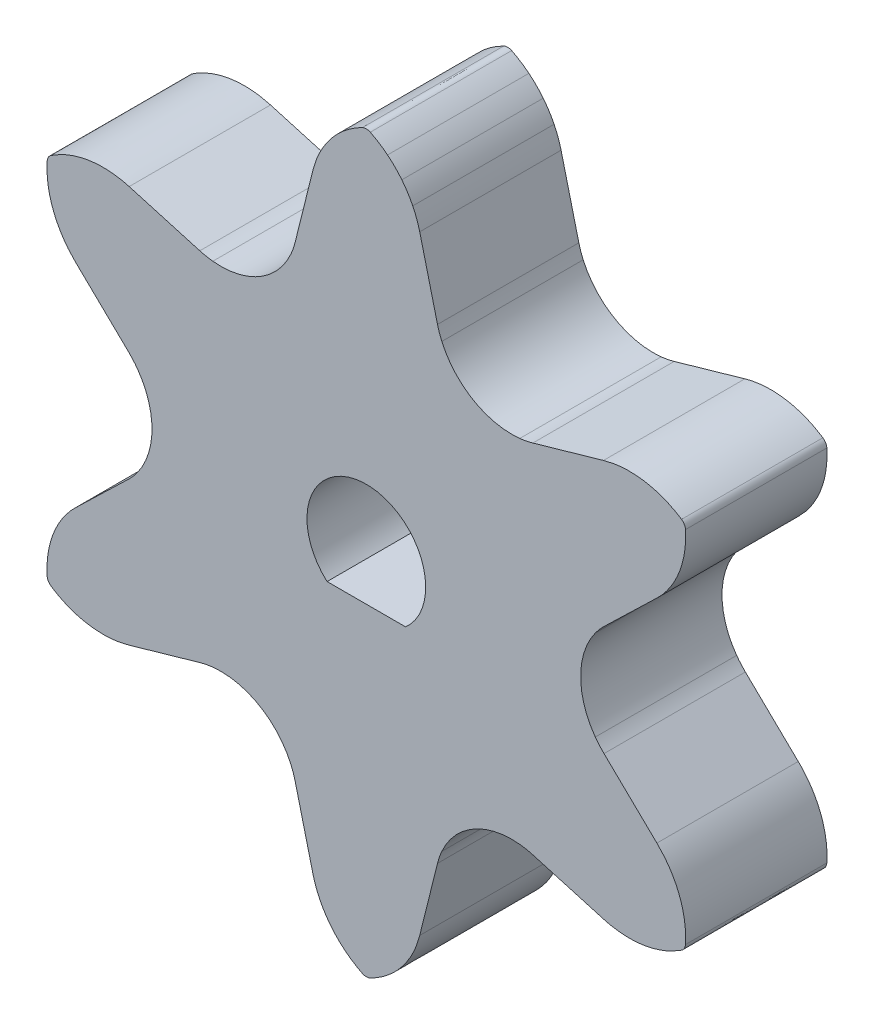
SolidWorks part; units mm, degrees
ref_plane "Front Plane" through (0, 0, 0) normal (0, 0, 1) x (1, 0, 0)
ref_plane "Top Plane" through (0, 0, 0) normal (0, 1, 0) x (1, 0, 0)
ref_plane "Right Plane" through (0, 0, 0) normal (1, 0, 0) x (0, 0, -1)
sketch "Sketch1" plane through (0, 0, 0) normal (0, 0, 1) x (1, 0, 0)
  line B0 (-1.3134, -1.475) -> (1.3134, -1.475)
  line B1 (1.7989, -10.2662) -> (2.3981, -7.8628)
  line B2 (-2.3981, -7.8628) -> (-1.7989, -10.2662)
  line B3 (9.7902, -3.5752) -> (8.0084, -1.8545)
  line B4 (5.6103, -6.0082) -> (7.9913, -6.691)
  line B5 (7.9913, 6.691) -> (5.6103, 6.0082)
  line B6 (8.0084, 1.8545) -> (9.7902, 3.5752)
  line B7 (-1.7989, 10.2662) -> (-2.3981, 7.8628)
  line B8 (2.3981, 7.8628) -> (1.7989, 10.2662)
  line B9 (-9.7902, 3.5752) -> (-8.0084, 1.8545)
  line B10 (-5.6103, 6.0082) -> (-7.9913, 6.691)
  line B11 (-7.9913, -6.691) -> (-5.6103, -6.0082)
  line B12 (-8.0084, -1.8545) -> (-9.7902, -3.5752)
  arc B13 (-2.5435, -7.44) -> (-5.1715, -5.9227) centre (-4.8997, -8.4865) ccw
  arc B14 (2.5435, -7.44) -> (2.3981, -7.8628) centre (4.8997, -8.4865) ccw
  arc B15 (0.1338, -12.34) -> (1.7989, -10.2662) centre (-1.2818, -9.4981) ccw
  arc B16 (-0.1338, -12.34) -> (0.1338, -12.34) centre (0, -12.0715) ccw
  arc B17 (-1.7989, -10.2662) -> (-0.1338, -12.34) centre (1.2818, -9.4981) ccw
  arc B18 (-2.3981, -7.8628) -> (-2.5435, -7.44) centre (-4.8997, -8.4865) ccw
  arc B19 (5.1715, -5.9227) -> (2.5435, -7.44) centre (4.8997, -8.4865) ccw
  arc B20 (7.715, -1.5173) -> (8.0084, -1.8545) centre (9.7993, 0) ccw
  arc B21 (10.7537, -6.0542) -> (9.7902, -3.5752) centre (7.5847, -5.8591) ccw
  arc B22 (10.6199, -6.2859) -> (10.7537, -6.0542) centre (10.4542, -6.0358) ccw
  arc B23 (7.9913, -6.691) -> (10.6199, -6.2859) centre (8.8664, -3.639) ccw
  arc B24 (5.6103, -6.0082) -> (5.1715, -5.9227) centre (4.8997, -8.4865) ccw
  arc B25 (7.715, 1.5173) -> (7.715, -1.5173) centre (9.7993, 0) ccw
  arc B26 (5.1715, 5.9227) -> (5.6103, 6.0082) centre (4.8997, 8.4865) ccw
  arc B27 (10.6199, 6.2859) -> (7.9913, 6.691) centre (8.8664, 3.639) ccw
  arc B28 (10.7537, 6.0542) -> (10.6199, 6.2859) centre (10.4542, 6.0358) ccw
  arc B29 (9.7902, 3.5752) -> (10.7537, 6.0542) centre (7.5847, 5.8591) ccw
  arc B30 (8.0084, 1.8545) -> (7.715, 1.5173) centre (9.7993, 0) ccw
  arc B31 (2.5435, 7.44) -> (5.1715, 5.9227) centre (4.8997, 8.4865) ccw
  arc B32 (-2.5435, 7.44) -> (-2.3981, 7.8628) centre (-4.8997, 8.4865) ccw
  arc B33 (-0.1338, 12.34) -> (-1.7989, 10.2662) centre (1.2818, 9.4981) ccw
  arc B34 (0.1338, 12.34) -> (-0.1338, 12.34) centre (0, 12.0715) ccw
  arc B35 (1.7989, 10.2662) -> (0.1338, 12.34) centre (-1.2818, 9.4981) ccw
  arc B36 (2.3981, 7.8628) -> (2.5435, 7.44) centre (4.8997, 8.4865) ccw
  arc B37 (-5.1715, 5.9227) -> (-2.5435, 7.44) centre (-4.8997, 8.4865) ccw
  arc B38 (-7.715, -1.5173) -> (-7.715, 1.5173) centre (-9.7993, 0) ccw
  arc B39 (-7.715, 1.5173) -> (-8.0084, 1.8545) centre (-9.7993, 0) ccw
  arc B40 (-10.7537, 6.0542) -> (-9.7902, 3.5752) centre (-7.5847, 5.8591) ccw
  arc B41 (-10.6199, 6.2859) -> (-10.7537, 6.0542) centre (-10.4542, 6.0358) ccw
  arc B42 (-7.9913, 6.691) -> (-10.6199, 6.2859) centre (-8.8664, 3.639) ccw
  arc B43 (-5.6103, 6.0082) -> (-5.1715, 5.9227) centre (-4.8997, 8.4865) ccw
  arc B44 (-5.1715, -5.9227) -> (-5.6103, -6.0082) centre (-4.8997, -8.4865) ccw
  arc B45 (-10.6199, -6.2859) -> (-7.9913, -6.691) centre (-8.8664, -3.639) ccw
  arc B46 (-10.7537, -6.0542) -> (-10.6199, -6.2859) centre (-10.4542, -6.0358) ccw
  arc B47 (-9.7902, -3.5752) -> (-10.7537, -6.0542) centre (-7.5847, -5.8591) ccw
  arc B48 (-8.0084, -1.8545) -> (-7.715, -1.5173) centre (-9.7993, 0) ccw
  arc B49 (1.3134, -1.475) -> (-1.3134, -1.475) centre (0, 0) ccw
  arc B50 (7.715, 1.5173) -> (7.715, -1.5173) centre (9.7993, 0) ccw
  arc B51 (2.5435, 7.44) -> (5.1715, 5.9227) centre (4.8997, 8.4865) ccw
  arc B52 (-2.5435, -7.44) -> (-5.1715, -5.9227) centre (-4.8997, -8.4865) ccw
  arc B53 (-5.1715, 5.9227) -> (-2.5435, 7.44) centre (-4.8997, 8.4865) ccw
  arc B54 (5.1715, -5.9227) -> (2.5435, -7.44) centre (4.8997, -8.4865) ccw
  arc B55 (-7.715, -1.5173) -> (-7.715, 1.5173) centre (-9.7993, 0) ccw
  spline B56 degree 3 poles (8.0084, -1.8545) (7.901, -1.7508) (7.8031, -1.6384) (7.715, -1.5173) knots 0 0 0 0 1 1 1 1
  spline B57 degree 3 poles (9.7902, -3.5752) (9.1967, -3.002) (8.6029, -2.4286) (8.0084, -1.8545) knots 0 0 0 0 1 1 1 1
  spline B58 degree 3 poles (10.7537, -6.0542) (10.7679, -5.8229) (10.7568, -5.5947) (10.6865, -5.1439) (10.6259, -4.9191) (10.4604, -4.4943) (10.3558, -4.2926) (10.1023, -3.9112) (9.9552, -3.7345) (9.7902, -3.5752) knots 0 0 0 0 0.25 0.25 0.5 0.5 0.75 0.75 1 1 1 1
  spline B59 degree 3 poles (10.7537, -6.0542) (10.7479, -6.147) (10.6975, -6.2345) (10.6199, -6.2859) knots 0 0 0 0 1 1 1 1
  spline B60 degree 3 poles (7.9913, -6.691) (8.2118, -6.7542) (8.4354, -6.7927) (8.8883, -6.822) (9.1203, -6.812) (9.5709, -6.7432) (9.791, -6.6851) (10.2204, -6.52) (10.4267, -6.4138) (10.6199, -6.2859) knots 0 0 0 0 0.25 0.25 0.5 0.5 0.75 0.75 1 1 1 1
  spline B61 degree 3 poles (7.9913, -6.691) (7.1982, -6.4635) (6.4046, -6.236) (5.6103, -6.0082) knots 0 0 0 0 1 1 1 1
  spline B62 degree 3 poles (5.1715, -5.9227) (5.3205, -5.9385) (5.4667, -5.9671) (5.6103, -6.0082) knots 0 0 0 0 1 1 1 1
  spline B63 degree 3 poles (-2.3981, 7.8628) (-2.4343, 7.7178) (-2.4827, 7.5769) (-2.5435, 7.44) knots 0 0 0 0 1 1 1 1
  spline B64 degree 3 poles (-1.7989, 10.2662) (-1.9985, 9.4656) (-2.1982, 8.6646) (-2.3981, 7.8628) knots 0 0 0 0 1 1 1 1
  spline B65 degree 3 poles (-0.1338, 12.34) (-0.3411, 12.2367) (-0.5333, 12.113) (-0.8885, 11.8267) (-1.0529, 11.6618) (-1.338, 11.3061) (-1.4604, 11.1147) (-1.664, 10.7045) (-1.7434, 10.4887) (-1.7989, 10.2662) knots 0 0 0 0 0.25 0.25 0.5 0.5 0.75 0.75 1 1 1 1
  spline B66 degree 3 poles (-0.1338, 12.34) (-0.0505, 12.3815) (0.0505, 12.3815) (0.1338, 12.34) knots 0 0 0 0 1 1 1 1
  spline B67 degree 3 poles (1.7989, 10.2662) (1.7434, 10.4887) (1.665, 10.7016) (1.4639, 11.1085) (1.3392, 11.3044) (1.0543, 11.6603) (0.8939, 11.8218) (0.5363, 12.1111) (0.3412, 12.2367) (0.1338, 12.34) knots 0 0 0 0 0.25 0.25 0.5 0.5 0.75 0.75 1 1 1 1
  spline B68 degree 3 poles (1.7989, 10.2662) (1.9985, 9.4656) (2.1982, 8.6646) (2.3981, 7.8628) knots 0 0 0 0 1 1 1 1
  spline B69 degree 3 poles (2.5435, 7.44) (2.4827, 7.5769) (2.4343, 7.7178) (2.3981, 7.8628) knots 0 0 0 0 1 1 1 1
  spline B70 degree 3 poles (2.3981, -7.8628) (2.4343, -7.7178) (2.4827, -7.5769) (2.5435, -7.44) knots 0 0 0 0 1 1 1 1
  spline B71 degree 3 poles (1.7989, -10.2662) (1.9985, -9.4656) (2.1982, -8.6646) (2.3981, -7.8628) knots 0 0 0 0 1 1 1 1
  spline B72 degree 3 poles (0.1338, -12.34) (0.3411, -12.2367) (0.5333, -12.113) (0.8885, -11.8267) (1.0529, -11.6618) (1.338, -11.3061) (1.4604, -11.1147) (1.664, -10.7045) (1.7434, -10.4887) (1.7989, -10.2662) knots 0 0 0 0 0.25 0.25 0.5 0.5 0.75 0.75 1 1 1 1
  spline B73 degree 3 poles (0.1338, -12.34) (0.0505, -12.3815) (-0.0505, -12.3815) (-0.1338, -12.34) knots 0 0 0 0 1 1 1 1
  spline B74 degree 3 poles (-1.7989, -10.2662) (-1.7434, -10.4887) (-1.665, -10.7016) (-1.4639, -11.1085) (-1.3392, -11.3044) (-1.0543, -11.6603) (-0.8939, -11.8218) (-0.5363, -12.1111) (-0.3412, -12.2367) (-0.1338, -12.34) knots 0 0 0 0 0.25 0.25 0.5 0.5 0.75 0.75 1 1 1 1
  spline B75 degree 3 poles (-1.7989, -10.2662) (-1.9985, -9.4656) (-2.1982, -8.6646) (-2.3981, -7.8628) knots 0 0 0 0 1 1 1 1
  spline B76 degree 3 poles (-2.5435, -7.44) (-2.4827, -7.5769) (-2.4343, -7.7178) (-2.3981, -7.8628) knots 0 0 0 0 1 1 1 1
  spline B77 degree 3 poles (-8.0084, 1.8545) (-7.901, 1.7508) (-7.8031, 1.6384) (-7.715, 1.5173) knots 0 0 0 0 1 1 1 1
  spline B78 degree 3 poles (-9.7902, 3.5752) (-9.1967, 3.002) (-8.6029, 2.4286) (-8.0084, 1.8545) knots 0 0 0 0 1 1 1 1
  spline B79 degree 3 poles (-10.7537, 6.0542) (-10.7679, 5.8229) (-10.7568, 5.5947) (-10.6865, 5.1439) (-10.6259, 4.9191) (-10.4604, 4.4943) (-10.3558, 4.2926) (-10.1023, 3.9112) (-9.9552, 3.7345) (-9.7902, 3.5752) knots 0 0 0 0 0.25 0.25 0.5 0.5 0.75 0.75 1 1 1 1
  spline B80 degree 3 poles (-10.7537, 6.0542) (-10.7479, 6.147) (-10.6975, 6.2345) (-10.6199, 6.2859) knots 0 0 0 0 1 1 1 1
  spline B81 degree 3 poles (-7.9913, 6.691) (-8.2118, 6.7542) (-8.4354, 6.7927) (-8.8883, 6.822) (-9.1203, 6.812) (-9.5709, 6.7432) (-9.791, 6.6851) (-10.2204, 6.52) (-10.4267, 6.4138) (-10.6199, 6.2859) knots 0 0 0 0 0.25 0.25 0.5 0.5 0.75 0.75 1 1 1 1
  spline B82 degree 3 poles (-7.9913, 6.691) (-7.1982, 6.4635) (-6.4046, 6.236) (-5.6103, 6.0082) knots 0 0 0 0 1 1 1 1
  spline B83 degree 3 poles (-5.1715, 5.9227) (-5.3205, 5.9385) (-5.4667, 5.9671) (-5.6103, 6.0082) knots 0 0 0 0 1 1 1 1
  spline B84 degree 3 poles (5.6103, 6.0082) (5.4667, 5.9671) (5.3205, 5.9385) (5.1715, 5.9227) knots 0 0 0 0 1 1 1 1
  spline B85 degree 3 poles (7.9913, 6.691) (7.1982, 6.4635) (6.4046, 6.236) (5.6103, 6.0082) knots 0 0 0 0 1 1 1 1
  spline B86 degree 3 poles (10.6199, 6.2859) (10.4268, 6.4138) (10.2235, 6.5184) (9.798, 6.6828) (9.573, 6.7427) (9.1224, 6.8118) (8.8955, 6.8221) (8.4383, 6.7933) (8.2118, 6.7542) (7.9913, 6.691) knots 0 0 0 0 0.25 0.25 0.5 0.5 0.75 0.75 1 1 1 1
  spline B87 degree 3 poles (10.6199, 6.2859) (10.6975, 6.2345) (10.7479, 6.147) (10.7537, 6.0542) knots 0 0 0 0 1 1 1 1
  spline B88 degree 3 poles (9.7902, 3.5752) (9.9552, 3.7345) (10.1004, 3.9089) (10.3522, 4.2865) (10.4595, 4.4924) (10.6253, 4.9171) (10.6849, 5.1368) (10.7567, 5.5911) (10.7679, 5.8229) (10.7537, 6.0542) knots 0 0 0 0 0.25 0.25 0.5 0.5 0.75 0.75 1 1 1 1
  spline B89 degree 3 poles (8.0084, 1.8545) (8.6029, 2.4286) (9.1967, 3.002) (9.7902, 3.5752) knots 0 0 0 0 1 1 1 1
  spline B90 degree 3 poles (7.715, 1.5173) (7.8031, 1.6384) (7.901, 1.7508) (8.0084, 1.8545) knots 0 0 0 0 1 1 1 1
  spline B91 degree 3 poles (-7.9913, -6.691) (-7.1982, -6.4635) (-6.4046, -6.236) (-5.6103, -6.0082) knots 0 0 0 0 1 1 1 1
  spline B92 degree 3 poles (-10.6199, -6.2859) (-10.4268, -6.4138) (-10.2235, -6.5184) (-9.798, -6.6828) (-9.573, -6.7427) (-9.1224, -6.8118) (-8.8955, -6.8221) (-8.4383, -6.7933) (-8.2118, -6.7542) (-7.9913, -6.691) knots 0 0 0 0 0.25 0.25 0.5 0.5 0.75 0.75 1 1 1 1
  spline B93 degree 3 poles (-10.6199, -6.2859) (-10.6975, -6.2345) (-10.7479, -6.147) (-10.7537, -6.0542) knots 0 0 0 0 1 1 1 1
  spline B94 degree 3 poles (-9.7902, -3.5752) (-9.9552, -3.7345) (-10.1004, -3.9089) (-10.3522, -4.2865) (-10.4595, -4.4924) (-10.6253, -4.9171) (-10.6849, -5.1368) (-10.7567, -5.5911) (-10.7679, -5.8229) (-10.7537, -6.0542) knots 0 0 0 0 0.25 0.25 0.5 0.5 0.75 0.75 1 1 1 1
  spline B95 degree 3 poles (-8.0084, -1.8545) (-8.6029, -2.4286) (-9.1967, -3.002) (-9.7902, -3.5752) knots 0 0 0 0 1 1 1 1
  spline B96 degree 3 poles (-5.6103, -6.0082) (-5.4667, -5.9671) (-5.3205, -5.9385) (-5.1715, -5.9227) knots 0 0 0 0 1 1 1 1
  spline B97 degree 3 poles (-7.715, -1.5173) (-7.8031, -1.6384) (-7.901, -1.7508) (-8.0084, -1.8545) knots 0 0 0 0 1 1 1 1
sketch_block_instance "motorsprocket-1"
sketch_block "motorsprocket"
other "DetailItem3"
other "DetailItem4"
extrude "Boss-Extrude1" add sketch "Sketch1" along normal blind 4.7625 contours B38 B97 B12 B47 B93 B45 B11 B96 B13 B76 B2 B17 B74 B73 B15 B1 B70 B19 B62 B4 B23 B59 B21 B3 B56 B25 B90 B6 B29 B87 B27 B5 B84 B31 B69 B8 B35 B67 B66 B33 B7 B63 B37 B83 B10 B42 B80
sketch "Sketch2" plane through (0, 0, 4.7625) normal (0, 0, 1) x (1, 0, 0)
  line L0 (-1.3229, -1.5) -> (1.3229, -1.5)
  arc A0 (1.3229, -1.5) -> (-1.3229, -1.5) centre (0, 0) ccw
  dimension "D1" = 4
  dimension "D2" = 1.5
extrude "Cut-Extrude1" cut sketch "Sketch2" against normal blind 4.7625
